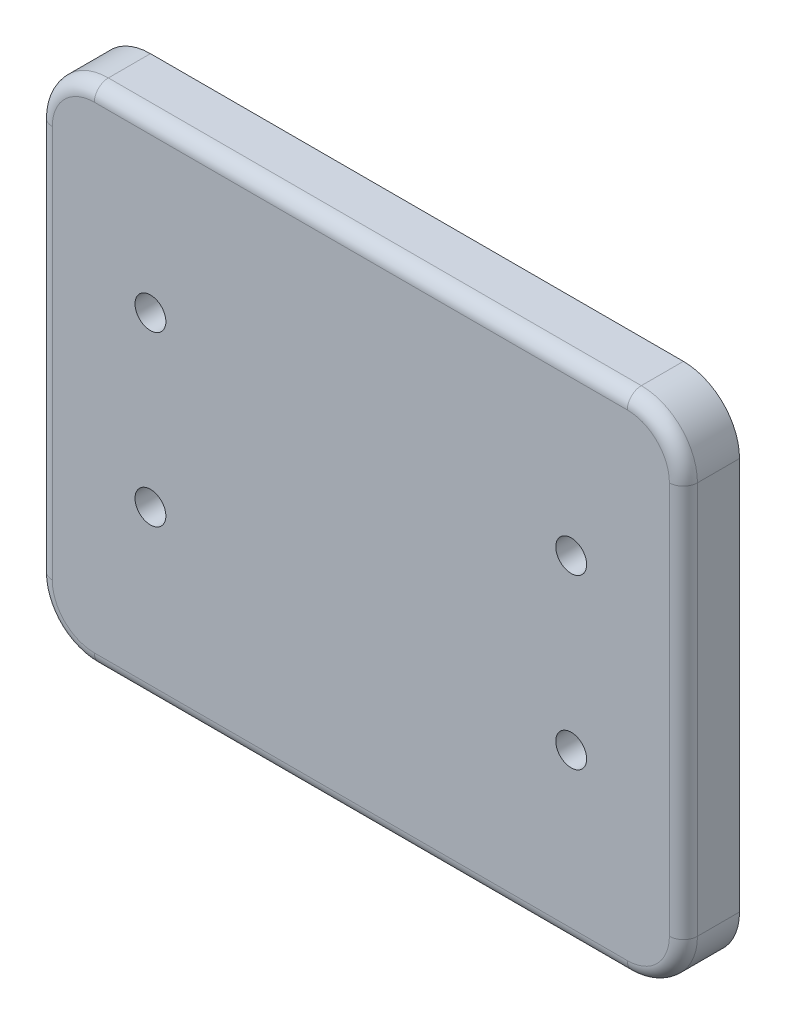
SolidWorks part; units mm, degrees
ref_plane "Front Plane" through (0, 0, 0) normal (0, 0, 1) x (1, 0, 0)
ref_plane "Top Plane" through (0, 0, 0) normal (0, 1, 0) x (1, 0, 0)
ref_plane "Right Plane" through (0, 0, 0) normal (1, 0, 0) x (0, 0, -1)
sketch "Sketch1" plane through (0, 0, 0) normal (0, 0, 1) x (1, 0, 0)
  line L1 (95, 90) -> (-95, 90)
  line L2 (115, 70) -> (115, -70)
  line L3 (95, -90) -> (-95, -90)
  line L4 (-115, 70) -> (-115, -70)
  line L5 (115, 90) -> (-115, -90) construction
  line L6 (115, -90) -> (-115, 90) construction
  arc A0 (-95, 90) -> (-115, 70) centre (-95, 70) ccw
  arc A1 (115, -70) -> (95, -90) centre (95, -70) cw
  arc A2 (95, 90) -> (115, 70) centre (95, 70) cw
  arc A3 (-95, -90) -> (-115, -70) centre (-95, -70) cw
  point P0 (0, 0)
  dimension "D3" = 20
  dimension "D1" = 180
  dimension "D2" = 230
extrude "Boss-Extrude1" add sketch "Sketch1" along normal blind 20
fillet "Fillet1" radius 5 8 edges at (0, 90, 20) (109.1421, 84.1421, 20) (115, 0, 20) (109.1421, -84.1421, 20) (0, -90, 20) (-109.1421, -84.1421, 20) (-115, 0, 20) (-109.1421, 84.1421, 20)
sketch "Sketch2" plane through (0, 0, 20) normal (0, 0, 1) x (1, 0, 0)
  circle A0 centre (-75, 30) radius 5.5
  circle A1 centre (75, 30) radius 5.5
  point P4 (0, 0)
  point P6 (0, 0)
  dimension "D4" = 11
  dimension "D1" = 30
  dimension "D2" = 75
  dimension "D3" = 75
extrude "Cut-Extrude1" cut sketch "Sketch2" against normal through all
sketch "Sketch3" plane through (0, 0, 0) normal (0, 0, -1) x (-1, 0, 0)
  circle A0 centre (-75, 30) radius 9
  circle A1 centre (75, 30) radius 9
  dimension "D1" = 18
extrude "Cut-Extrude2" cut sketch "Sketch3" against normal blind 11
mirror "Mirror1" about plane through (0, 0, 0) normal (0, 1, 0) of "Cut-Extrude2", "Cut-Extrude1"
